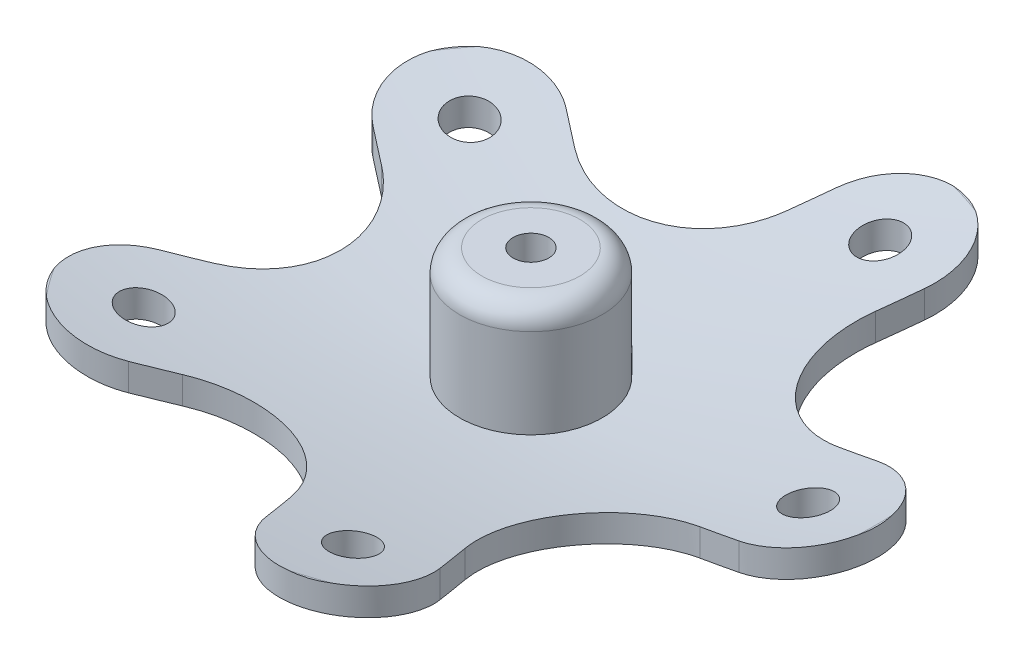
SolidWorks part; units mm, degrees
ref_plane "Front Plane" through (0, 0, 0) normal (0, 0, 1) x (1, 0, 0)
ref_plane "Top Plane" through (0, 0, 0) normal (0, 1, 0) x (1, 0, 0)
ref_plane "Right Plane" through (0, 0, 0) normal (1, 0, 0) x (0, 0, -1)
sketch "Sketch1" plane through (0, 0, 0) normal (0, 1, 0) x (1, 0, 0)
  circle A0 centre (0, 0) radius 4.8
extrude "Boss-Extrude1" add sketch "Sketch1" along normal blind 7.8 contours A0
sketch "Sketch2" plane through (0, 7.8, 0) normal (0, 1, 0) x (1, 0, 0)
  circle A0 centre (0, 0) radius 1.2
extrude "Cut-Extrude1" cut sketch "Sketch2" against normal blind 7.8
fillet "Fillet1" radius 1.5 1 edges at (0, 7.8, 4.8)
sketch "Sketch3" plane through (0, 0, 0) normal (0, -1, 0) x (1, 0, 0)
  line L0 (0.835, 0) -> (17.145, 0) construction
  line L1 (18.645, 4.65) -> (16.0348, 4.65)
  line L2 (18.645, -4.65) -> (16.0348, -4.65)
  line L3 (10.184, -16.2955) -> (9.3775, -13.8131)
  line L4 (1.3392, -19.1694) -> (0.5326, -16.687)
  line L5 (-12.3509, -14.7212) -> (-10.2393, -13.187)
  line L6 (-17.8173, -7.1973) -> (-15.7057, -5.6631)
  line L7 (-17.8173, 7.1973) -> (-15.7057, 5.6631)
  line L8 (-12.3509, 14.7212) -> (-10.2393, 13.187)
  line L9 (1.3392, 19.1694) -> (0.5326, 16.687)
  line L10 (10.184, 16.2955) -> (9.3775, 13.8131)
  circle A0 centre (0, 0) radius 0.835 construction
  circle A1 centre (18.645, 0) radius 1.5
  circle A2 centre (0, 0) radius 18.645 construction
  arc A3 (18.645, -4.65) -> (18.645, 4.65) centre (18.645, 0) ccw
  circle A4 centre (5.7616, -17.7324) radius 1.5
  arc A5 (1.3392, -19.1694) -> (10.184, -16.2955) centre (5.7616, -17.7324) ccw
  circle A6 centre (-15.0841, -10.9593) radius 1.5
  arc A7 (-17.8173, -7.1973) -> (-12.3509, -14.7212) centre (-15.0841, -10.9593) ccw
  circle A8 centre (-15.0841, 10.9593) radius 1.5
  arc A9 (-12.3509, 14.7212) -> (-17.8173, 7.1973) centre (-15.0841, 10.9593) ccw
  circle A10 centre (5.7616, 17.7324) radius 1.5
  arc A11 (10.184, 16.2955) -> (1.3392, 19.1694) centre (5.7616, 17.7324) ccw
  arc A12 (0.5326, -16.687) -> (-10.2393, -13.187) centre (-6.1248, -18.8501) ccw
  arc A13 (16.0348, -4.65) -> (9.3775, -13.8131) centre (16.0348, -11.65) ccw
  arc A14 (16.0348, 4.65) -> (9.3775, 13.8131) centre (16.0348, 11.65) cw
  arc A15 (0.5326, 16.687) -> (-10.2393, 13.187) centre (-6.1248, 18.8501) cw
  arc A16 (-15.7057, 5.6631) -> (-15.7057, -5.6631) centre (-19.8202, 0) cw
  point P44 (0, 0)
  dimension "D1" = 5
  dimension "D2" = 7
extrude "Boss-Extrude2" add sketch "Sketch3" along normal blind 1.8 and the other way blind 4
sketch "Sketch4" plane through (0, 0, 0) normal (1, 0, 0) x (0, 0, -1)
  line L8 (-4.65, -1.8) -> (4.65, -1.8) construction
  line L13 (-4.8, 6.3) -> (-4.8, 0.2891)
  line L14 (-4.8, 6.3) -> (-26.0597, 6.3)
  line L15 (-26.0597, 6.3) -> (-26.0597, -5.3176)
  line L16 (-26.0597, -5.3176) -> (0, -5.3176)
  line L17 (0, -5.3176) -> (0, -1.8)
  line L18 (0, 0) -> (0, 4.6222) construction
  line L19 (-23.586, 3.2262) -> (-23.586, 1.4722)
  line L20 (-23.182, 3.2262) -> (-23.586, 3.2262)
  spline S0 degree 3 poles (0, -1.8) (-4.4399, -1.6388) (-11.9501, -0.8817) (-19.7667, 0.6067) (-23.1852, 1.3799) (-23.586, 1.4722) knots 0 0 0 0 0.58933 1 1.054603 1.054603 1.054603 1.054603
  spline S1 degree 1 poles (0.0653, -0.0012) (-23.182, 3.2262) knots 0 0 1 1 construction
  spline S2 degree 3 poles (0.0653, -0.0012) (-1.8874, 0.0697) (-5.7873, 0.3236) (-11.6216, 1.0117) (-17.426, 1.9771) (-21.2695, 2.7858) (-23.182, 3.2262) knots 0 0 0 0 0.263651 0.527302 0.790952 1.054603 1.054603 1.054603 1.054603 only from (-4.8, 0.2891) to (-23.182, 3.2262)
  dimension "D1" = 1.8
revolve "Cut-Revolve1" cut sketch "Sketch4" angle 360 about L18
sketch "Sketch5" plane through (0, 4, 0) normal (0, 1, 0) x (1, 0, 0)
  circle A0 centre (0, 0) radius 0.75
extrude "Cut-Extrude2" cut sketch "Sketch5" against normal blind 29.4
